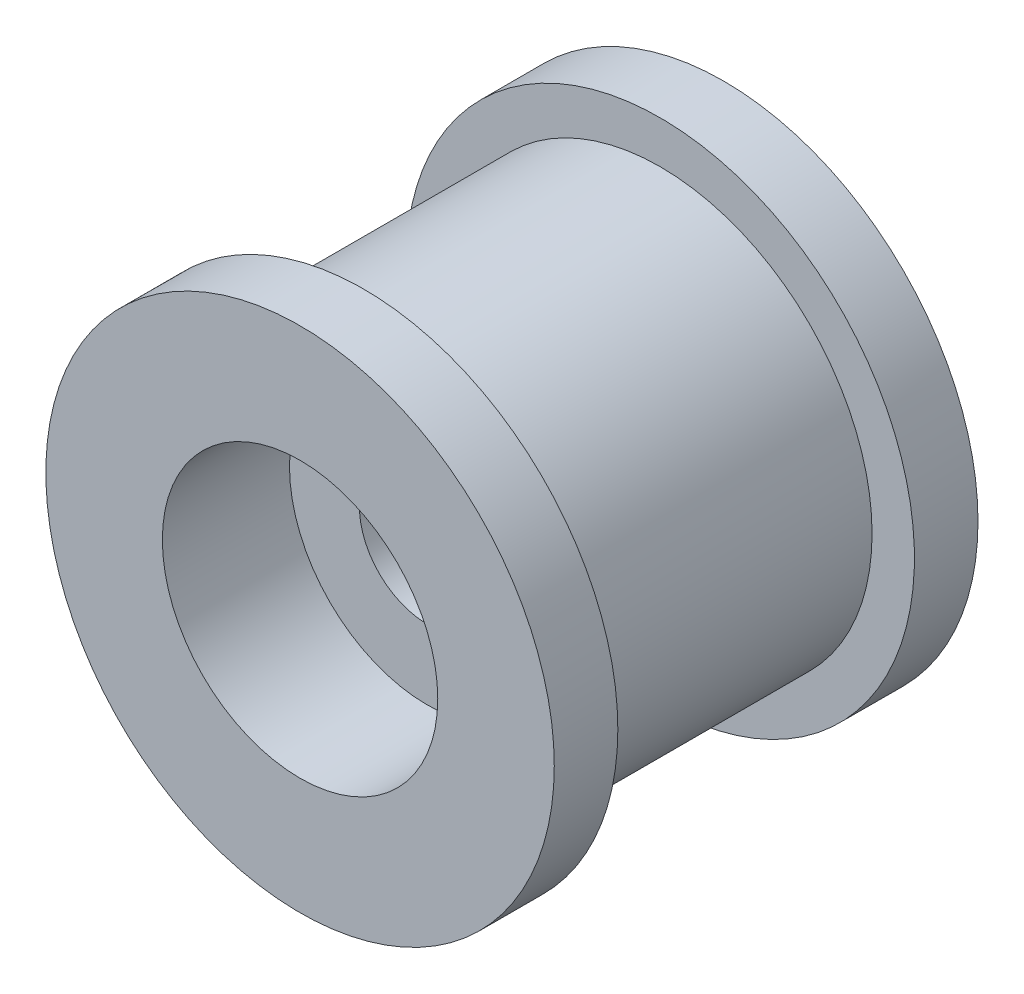
SolidWorks part; units mm, degrees
ref_plane "Front Plane" through (0, 0, 0) normal (0, 0, 1) x (1, 0, 0)
ref_plane "Top Plane" through (0, 0, 0) normal (0, 1, 0) x (1, 0, 0)
ref_plane "Right Plane" through (0, 0, 0) normal (1, 0, 0) x (0, 0, -1)
sketch "Sketch1" plane through (0, 0, 0) normal (0, 0, 1) x (1, 0, 0)
  circle A0 centre (0, 0) radius 1.6
  circle A1 centre (0, 0) radius 6
  dimension "D1" = 3.2
  dimension "D2" = 12
extrude "Boss-Extrude1" add sketch "Sketch1" along normal blind 10
sketch "Sketch2" plane through (0, 0, 0) normal (0, 1, 0) x (1, 0, 0)
  line L0 (0, 0) -> (0, -10) construction
  line L1 (-6.3324, -8.5) -> (-5, -8.5)
  line L2 (-6.3324, -8.5) -> (-6.3324, -1.5)
  line L3 (-6.3324, -1.5) -> (-5, -1.5)
  line L4 (-5, -8.5) -> (-5, -1.5)
  line L5 (-6.3324, -8.5) -> (-5, -1.5) construction
  line L6 (-6.3324, -1.5) -> (-5, -8.5) construction
  line L7 (-6, -10) -> (6, -10) construction
  line L8 (-5.6662, -5) -> (0, -5) construction
  point P0 (-5.6662, -5)
  dimension "D1" = 7
  dimension "D2" = 5
revolve "Cut-Revolve1" cut sketch "Sketch2" angle 360 about L0
sketch "Sketch4" plane through (0, 0, 10) normal (0, 0, 1) x (1, 0, 0)
  circle A0 centre (0, 0) radius 3.25
  dimension "D1" = 6.5
extrude "Cut-Extrude1" cut sketch "Sketch4" against normal blind 3
